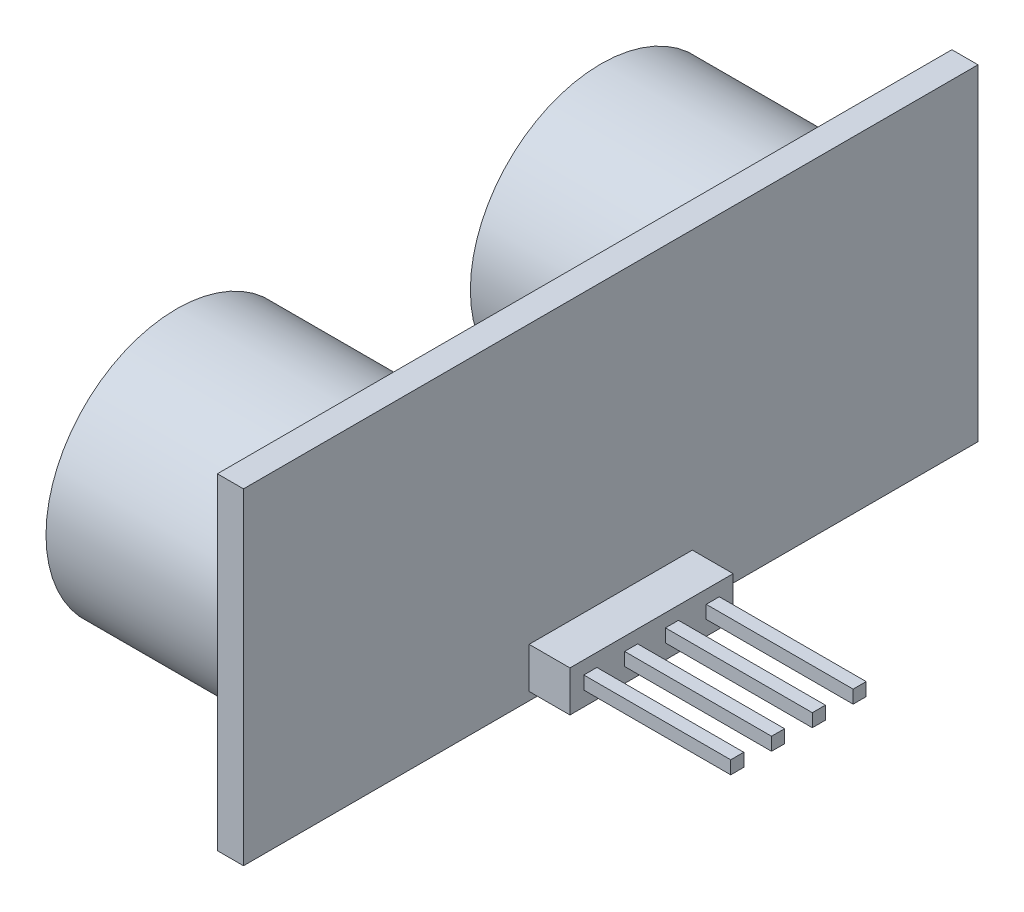
SolidWorks part; units mm, degrees
ref_plane "Front Plane" through (0, 0, 0) normal (0, 0, 1) x (1, 0, 0)
ref_plane "Top Plane" through (0, 0, 0) normal (0, 1, 0) x (1, 0, 0)
ref_plane "Right Plane" through (0, 0, 0) normal (1, 0, 0) x (0, 0, -1)
sketch "Sketch1" plane through (0, 0, 0) normal (0, 0, 1) x (1, 0, 0)
  line L1 (-0.8, -10) -> (0.8, -10)
  line L2 (-0.8, -10) -> (-0.8, 10)
  line L3 (-0.8, 10) -> (0.8, 10)
  line L4 (0.8, -10) -> (0.8, 10)
  line L5 (-0.8, -10) -> (0.8, 10) construction
  line L6 (-0.8, 10) -> (0.8, -10) construction
  point P0 (0, 0)
  dimension "D1" = 1.6
  dimension "D2" = 20
extrude "Boss-Extrude1" add sketch "Sketch1" along normal blind 45
sketch "Sketch2" plane through (0.8, 0, 0) normal (1, 0, 0) x (0, 0, -1)
  line L0 (0, -10) -> (0, 10) construction
  line L1 (-27.5, -7) -> (-17.5, -7)
  line L2 (-27.5, -7) -> (-27.5, -9.5)
  line L3 (-27.5, -9.5) -> (-17.5, -9.5)
  line L4 (-17.5, -7) -> (-17.5, -9.5)
  line L5 (-27.5, -7) -> (-17.5, -9.5) construction
  line L6 (-27.5, -9.5) -> (-17.5, -7) construction
  line L7 (-45, -10) -> (0, -10) construction
  point P0 (-22.5, -8.25)
  dimension "D1" = 2.5
  dimension "D2" = 10
  dimension "D3" = 22.5
  dimension "D4" = 0.5
extrude "Boss-Extrude2" add sketch "Sketch2" along normal blind 2.5
sketch "Sketch3" plane through (3.3, -6.2, 0) normal (-1, 0, 0) x (0, -1, 0)
  line L1 (1.6009, 26.65) -> (2.4009, 26.65)
  line L2 (1.6009, 26.65) -> (1.6009, 25.85)
  line L3 (1.6009, 25.85) -> (2.4009, 25.85)
  line L4 (2.4009, 26.65) -> (2.4009, 25.85)
  line L5 (1.6009, 26.65) -> (2.4009, 25.85) construction
  line L6 (1.6009, 25.85) -> (2.4009, 26.65) construction
  line L7 (1.6009, 24.15) -> (2.4009, 24.15)
  line L8 (1.6009, 24.15) -> (1.6009, 23.35)
  line L9 (1.6009, 23.35) -> (2.4009, 23.35)
  line L10 (2.4009, 24.15) -> (2.4009, 23.35)
  line L11 (1.6009, 24.15) -> (2.4009, 23.35) construction
  line L12 (1.6009, 23.35) -> (2.4009, 24.15) construction
  line L13 (1.6009, 21.65) -> (2.4009, 21.65)
  line L14 (1.6009, 21.65) -> (1.6009, 20.85)
  line L15 (1.6009, 20.85) -> (2.4009, 20.85)
  line L16 (2.4009, 21.65) -> (2.4009, 20.85)
  line L17 (1.6009, 21.65) -> (2.4009, 20.85) construction
  line L18 (1.6009, 20.85) -> (2.4009, 21.65) construction
  line L19 (1.6009, 19.15) -> (2.4009, 19.15)
  line L20 (1.6009, 19.15) -> (1.6009, 18.35)
  line L21 (1.6009, 18.35) -> (2.4009, 18.35)
  line L22 (2.4009, 19.15) -> (2.4009, 18.35)
  line L23 (1.6009, 19.15) -> (2.4009, 18.35) construction
  line L24 (1.6009, 18.35) -> (2.4009, 19.15) construction
  line L25 (0.8, 27.5) -> (3.3, 27.5) construction
  point P0 (2.0009, 26.25)
  point P8 (2.0009, 23.75)
  point P13 (2.0009, 21.25)
  point P18 (2.0009, 18.75)
  dimension "D1" = 0.8
  dimension "D2" = 0.8
  dimension "D3" = 1.25
  dimension "D4" = 4
extrude "Boss-Extrude3" add sketch "Sketch3" against normal blind 9
sketch "Sketch4" plane through (-0.8, 0, 0) normal (-1, 0, 0) x (0, 0, 1)
  line L0 (45, -10) -> (0, -10) construction
  line L1 (22.5, -10) -> (22.5, -7.8646) construction
  circle A0 centre (9.5, 0) radius 8
  circle A1 centre (35.5, 0) radius 8
  dimension "D1" = 16
  dimension "D2" = 16
  dimension "D3" = 10
  dimension "D4" = 26
  dimension "D5" = 13
extrude "Boss-Extrude4" add sketch "Sketch4" along normal blind 12
sketch "Sketch5" plane through (-12.8, 0, 0) normal (-1, 0, 0) x (0, 0, 1)
  circle A5 centre (35.5, 0) radius 7
  circle A6 centre (35.5, 0) radius 7
  circle A7 centre (9.5, 0) radius 7
  circle A8 centre (9.5, 0) radius 7
  dimension "D1" = 1
  dimension "D2" = 1
extrude "Cut-Extrude1" cut sketch "Sketch5" against normal blind 1
